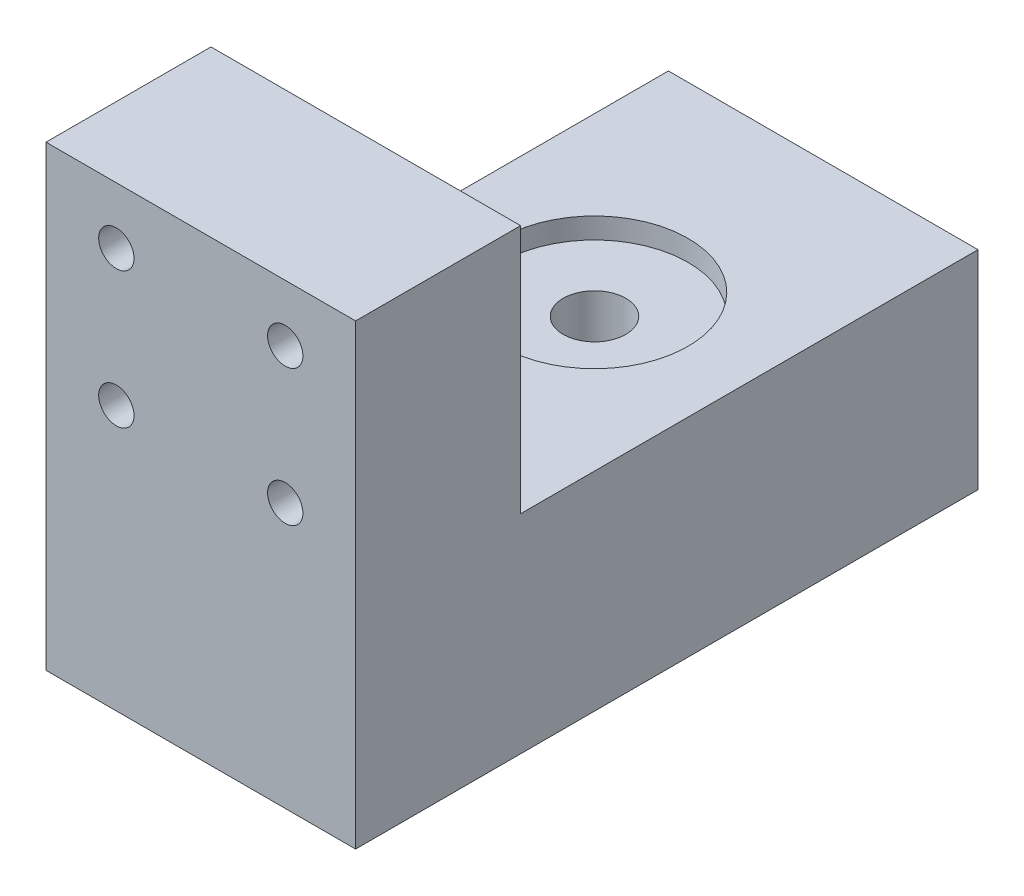
SolidWorks part; units mm, degrees
ref_plane "Front Plane" through (0, 0, 0) normal (0, 0, 1) x (1, 0, 0)
ref_plane "Top Plane" through (0, 0, 0) normal (0, 1, 0) x (1, 0, 0)
ref_plane "Right Plane" through (0, 0, 0) normal (1, 0, 0) x (0, 0, -1)
sketch "Sketch1" plane through (0, 0, 0) normal (0, 0, 1) x (1, 0, 0)
  line L1 (14.89, -10) -> (-14.89, -10)
  line L2 (14.89, -10) -> (14.89, 10)
  line L3 (14.89, 10) -> (-14.89, 10)
  line L4 (-14.89, -10) -> (-14.89, 10)
  line L5 (14.89, -10) -> (-14.89, 10) construction
  line L6 (14.89, 10) -> (-14.89, -10) construction
  point P0 (0, 0)
  dimension "D1" = 20
  dimension "D2" = 29.78
extrude "Boss-Extrude2" add sketch "Sketch1" along normal blind 44 contours L3 L4 L1 L2
sketch "Sketch4" plane through (0, 0, 44) normal (0, 0, 1) x (1, 0, 0)
  line L0 (14.89, -10) -> (14.89, 10) construction
  line L1 (-14.89, -10) -> (14.89, -10)
  line L2 (-14.89, -10) -> (-14.89, 34)
  line L3 (-14.89, 34) -> (14.89, 34)
  line L4 (14.89, -10) -> (14.89, 34)
  dimension "D1" = 44
extrude "Boss-Extrude3" add sketch "Sketch4" along normal blind 15.87 contours L3 L4 L1 L2
sketch "Sketch5" plane through (0, 10, 0) normal (0, 1, 0) x (1, 0, 0)
  circle A0 centre (0, -22) radius 9
  dimension "D1" = 18
extrude "Cut-Extrude1" cut sketch "Sketch5" against normal blind 2 contours A0
sketch "Sketch7" plane through (0, 8, 0) normal (0, 1, 0) x (1, 0, 0)
  circle A0 centre (0, -22) radius 3.0125
  dimension "D1" = 6.025
extrude "Cut-Extrude2" cut sketch "Sketch7" against normal through all contours A0
sketch "Sketch8" plane through (0, 0, 44) normal (0, 0, -1) x (-1, 0, 0)
  line L1 (-14.89, 34) -> (14.89, 34)
  line L2 (-14.89, 34) -> (-14.89, 10)
  line L3 (-14.89, 10) -> (14.89, 10)
  line L4 (14.89, 34) -> (14.89, 10)
  circle A0 centre (-8.1237, 28.547) radius 1.7
  circle A1 centre (8.1237, 28.547) radius 1.7
  circle A3 centre (-8.1237, 15.453) radius 1.7
  circle A4 centre (8.1237, 15.453) radius 1.7
  dimension "D1" = 3.4
extrude "Cut-Extrude3" cut sketch "Sketch8" against normal through all contours A0 | A3 | A4 | A1
equation "\"h\"= 20"
equation "\"E\"= 2145"
equation "\"M\"= 13200"
equation "\"S_all\"= 50 / 3"
equation "\"c\" = \"h\" / 2"
equation "\"L\"= 44"
equation "\"def\"= .30"
equation "\"b\"= ( 6 * \"M\" * \"L\" ^ 2 ) / ( \"E\" * \"def\" * \"h\" ^ 3 )"
equation "\"h2\"= ( ( 6 * \"M\" * \"L\" ^ 2 ) / ( 2 * \"E\" * \"def\" * \"b\" ) ) ^ ( 1 / 3 )"
